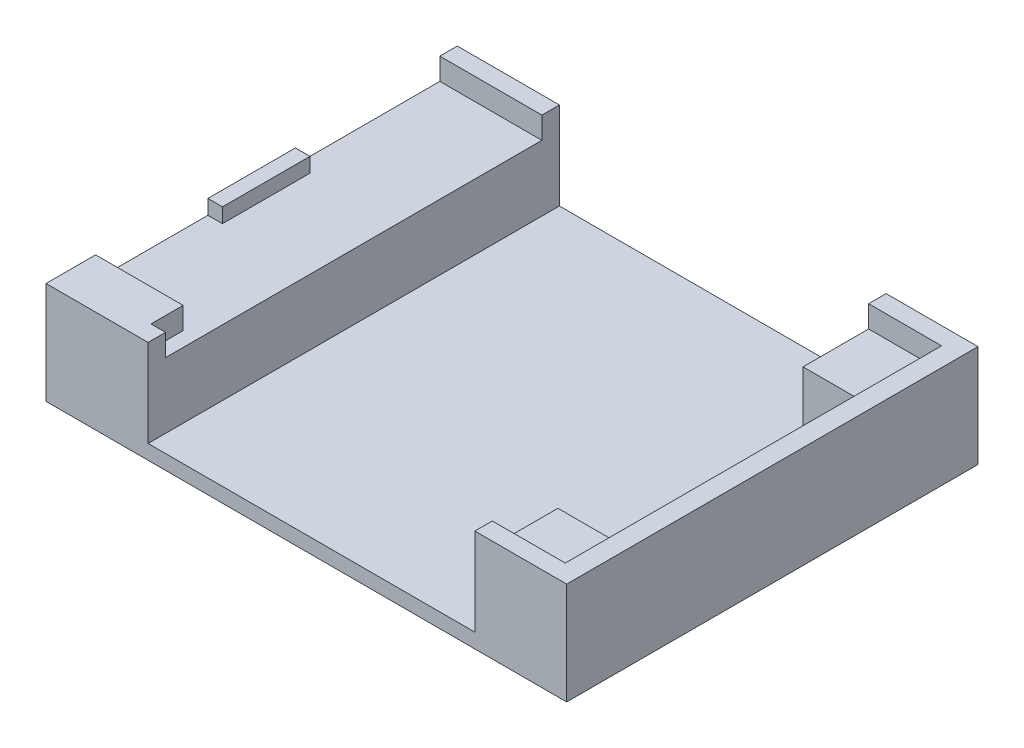
SolidWorks part; units mm, degrees
ref_plane "Front Plane" through (0, 0, 0) normal (0, 0, 1) x (1, 0, 0)
ref_plane "Top Plane" through (0, 0, 0) normal (0, 1, 0) x (1, 0, 0)
ref_plane "Right Plane" through (0, 0, 0) normal (1, 0, 0) x (0, 0, -1)
sketch "Sketch1" plane through (0, 0, 0) normal (0, 1, 0) x (1, 0, 0)
  line L1 (-17.85, 14.1) -> (17.85, 14.1)
  line L2 (-17.85, 14.1) -> (-17.85, -14.1)
  line L3 (-17.85, -14.1) -> (17.85, -14.1)
  line L4 (17.85, 14.1) -> (17.85, -14.1)
  line L5 (-17.85, 14.1) -> (17.85, -14.1) construction
  line L6 (-17.85, -14.1) -> (17.85, 14.1) construction
  point P0 (0, 0)
  dimension "D1" = 35.7
  dimension "D2" = 28.2
extrude "Boss-Extrude1" add sketch "Sketch1" along normal blind 7
sketch "Sketch2" plane through (0, 7, 0) normal (0, 1, 0) x (1, 0, 0)
  line L0 (-17.85, 14.1) -> (-17.85, -14.1) construction
  line L1 (-17.85, 12.9) -> (16.55, 12.9)
  line L2 (-17.85, 12.9) -> (-17.85, -12.9)
  line L3 (-17.85, -12.9) -> (16.55, -12.9)
  line L4 (16.55, 12.9) -> (16.55, -12.9)
  line L5 (17.85, 0) -> (-17.85, 0) construction
  dimension "D1" = 25.8
  dimension "D2" = 34.4
extrude "Cut-Extrude1" cut sketch "Sketch2" against normal blind 1.5
sketch "Sketch3" plane through (0, 5.5, 0) normal (0, 1, 0) x (1, 0, 0)
  line L0 (-10.85, 12.9) -> (-10.85, -12.9)
  line L1 (16.55, 12.9) -> (-17.85, 12.9) construction
  line L2 (-17.85, -12.9) -> (16.55, -12.9) construction
  line L3 (-10.85, -12.9) -> (11.55, -12.9)
  line L4 (-17.85, -12.9) -> (16.55, -12.9) construction
  line L5 (11.55, -12.9) -> (11.55, -8.4)
  line L6 (11.55, -8.4) -> (16.55, -8.4)
  line L7 (16.55, -12.9) -> (16.55, 12.9) construction
  line L8 (16.55, -8.4) -> (16.55, 8.4)
  line L9 (16.55, 8.4) -> (11.55, 8.4)
  line L10 (11.55, 8.4) -> (11.55, 12.9)
  line L11 (11.55, 12.9) -> (-10.85, 12.9)
  line L12 (-17.85, 12.9) -> (-17.85, -12.9) construction
  dimension "D1" = 5
  dimension "D2" = 5
  dimension "D3" = 4.5
  dimension "D4" = 4.5
  dimension "D5" = 7
extrude "Cut-Extrude2" cut sketch "Sketch3" against normal offset from surface (4.5 mm away) 1 up to face at (0, 0, 0)
sketch "Sketch4" plane through (0, 7, 0) normal (0, 1, 0) x (1, 0, 0)
  line L0 (-17.85, -14.1) -> (17.85, -14.1) construction
  line L1 (-10.85, -12.9) -> (11.55, -12.9)
  line L2 (-10.85, -12.9) -> (-10.85, -14.1)
  line L3 (-10.85, -14.1) -> (11.55, -14.1)
  line L4 (11.55, -12.9) -> (11.55, -14.1)
  line L5 (11.55, -8.4) -> (11.55, -12.9) construction
extrude "Cut-Extrude3" cut sketch "Sketch4" against normal up to surface (6 mm away) up to face at (7.2, 1, 0)
mirror "Mirror1" about plane through (0, 0, 0) normal (0, 0, 1) of "Cut-Extrude3"
sketch "Sketch5" plane through (0, 5.5, 0) normal (0, 1, 0) x (1, 0, 0)
  line L0 (-17.85, 12.9) -> (-17.85, -12.9) construction
  line L1 (-17.85, 3) -> (-16.85, 3)
  line L2 (-17.85, 3) -> (-17.85, -3)
  line L3 (-17.85, -3) -> (-16.85, -3)
  line L4 (-16.85, 3) -> (-16.85, -3)
  point P6 (-16.85, 0)
  dimension "D1" = 6
  dimension "D2" = 1
extrude "Boss-Extrude2" add sketch "Sketch5" along normal blind 1
sketch "Sketch6" plane through (0, 5.5, 0) normal (0, 1, 0) x (1, 0, 0)
  line L0 (-11.85, -12.9) -> (-11.85, -10.7)
  line L1 (-17.85, -12.9) -> (-10.85, -12.9) construction
  line L2 (-11.85, -10.7) -> (-17.85, -10.7)
  line L3 (-17.85, -3) -> (-17.85, -12.9) construction
  line L4 (-17.85, -10.7) -> (-17.85, -12.9)
  line L5 (-17.85, -12.9) -> (-11.85, -12.9)
  dimension "D1" = 6
  dimension "D2" = 2.2
extrude "Boss-Extrude3" add sketch "Sketch6" along normal blind 1.5
